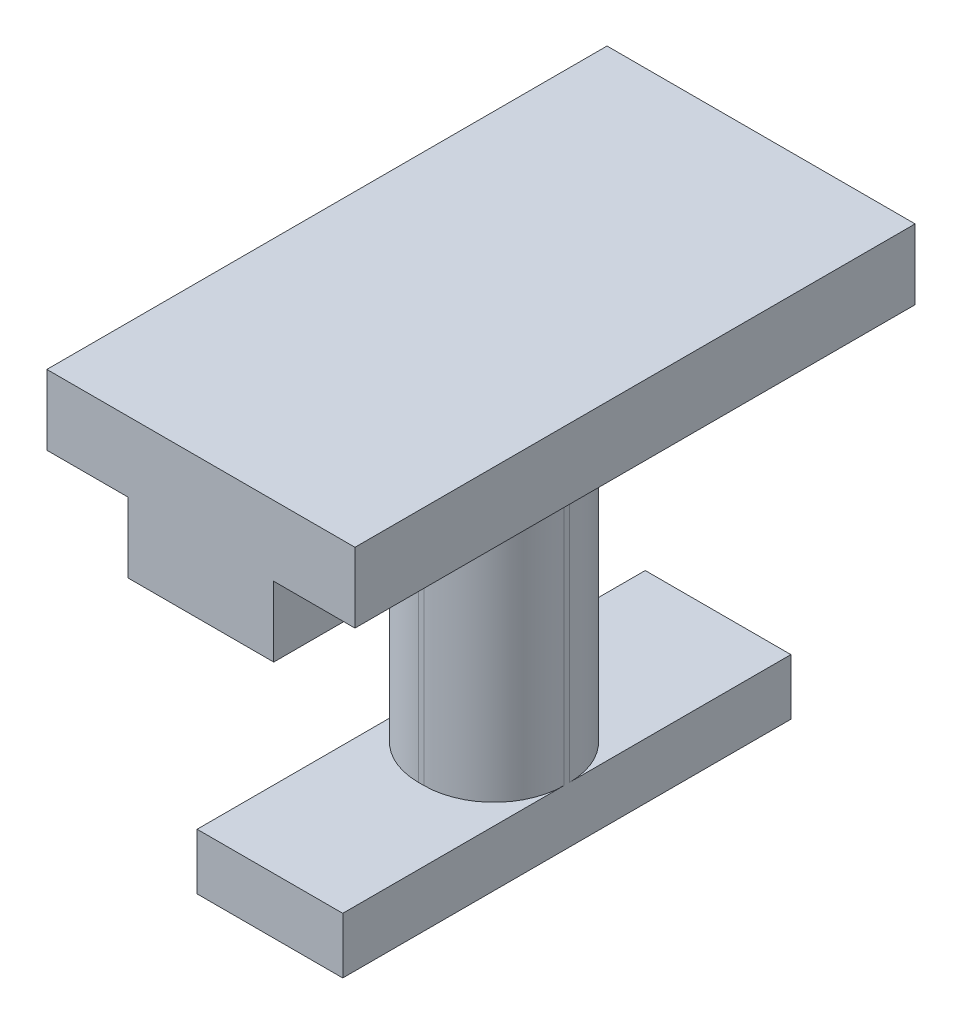
SolidWorks part; units mm, degrees
ref_plane "Alzado" through (0, 0, 0) normal (0, 0, 1) x (1, 0, 0)
ref_plane "Planta" through (0, 0, 0) normal (0, 1, 0) x (1, 0, 0)
ref_plane "Vista lateral" through (0, 0, 0) normal (1, 0, 0) x (0, 0, -1)
sketch "Croquis1" plane through (0, 0, 0) normal (0, 0, 1) x (1, 0, 0)
  line L0 (-5.5, 0) -> (5.5, 0)
  line L1 (5.5, 0) -> (5.5, -2.5)
  line L2 (5.5, -2.5) -> (2.6, -2.5)
  line L3 (2.6, -2.5) -> (2.6, -5)
  line L4 (2.6, -5) -> (-2.6, -5)
  line L5 (0, 0) -> (0, -5) construction
  line L6 (-2.6, -2.5) -> (-2.6, -5)
  line L7 (-5.5, -2.5) -> (-2.6, -2.5)
  line L8 (-5.5, 0) -> (-5.5, -2.5)
  dimension "D1" = 5.5
  dimension "D2" = 2.5
  dimension "D3" = 2.5
  dimension "D4" = 2.9
extrude "Saliente-Extruir1" add sketch "Croquis1" along normal blind 20
sketch "Croquis2" plane through (0, -5, 0) normal (0, -1, 0) x (1, 0, 0)
  line L2 (-2.6, 6.9359) -> (2.6, 6.9359)
  line L3 (-2.6, 6.9359) -> (-2.6, 12.1359)
  line L4 (2.6, 6.9359) -> (2.6, 12.1359)
  line L5 (-2.6, 12.1359) -> (2.6, 12.1359)
  line L6 (-2.6, 6.9359) -> (2.6, 12.1359) construction
  line L7 (2.6, 6.9359) -> (-2.6, 12.1359) construction
  dimension "D1" = 5.2
  dimension "D2" = 5.2
extrude "Saliente-Extruir2" add sketch "Croquis2" along normal blind 9
sketch "Croquis3" plane through (0, -14, 0) normal (0, -1, 0) x (1, 0, 0)
  line L0 (2.6, 17.5359) -> (-2.6, 17.5359)
  line L1 (2.6, 6.9359) -> (2.6, 0) construction
  line L2 (-2.6, 20) -> (-2.6, 12.1359) construction
  line L3 (2.6, 20) -> (2.6, 0) construction
  line L4 (2.6, 1.5359) -> (2.6, 17.5359)
  line L5 (-2.6, 17.5359) -> (-2.6, 1.5359)
  line L6 (-2.6, 20) -> (-2.6, 0) construction
  line L7 (-2.6, 1.5359) -> (2.6, 1.5359)
  dimension "D1" = 16
extrude "Saliente-Extruir4" add sketch "Croquis3" along normal blind 2
fillet "Redondeo4" radius 2.5 4 edges at (-2.6, -9.5, 12.1359) (-2.6, -9.5, 6.9359) (2.6, -9.5, 12.1359) (2.6, -9.5, 6.9359)
